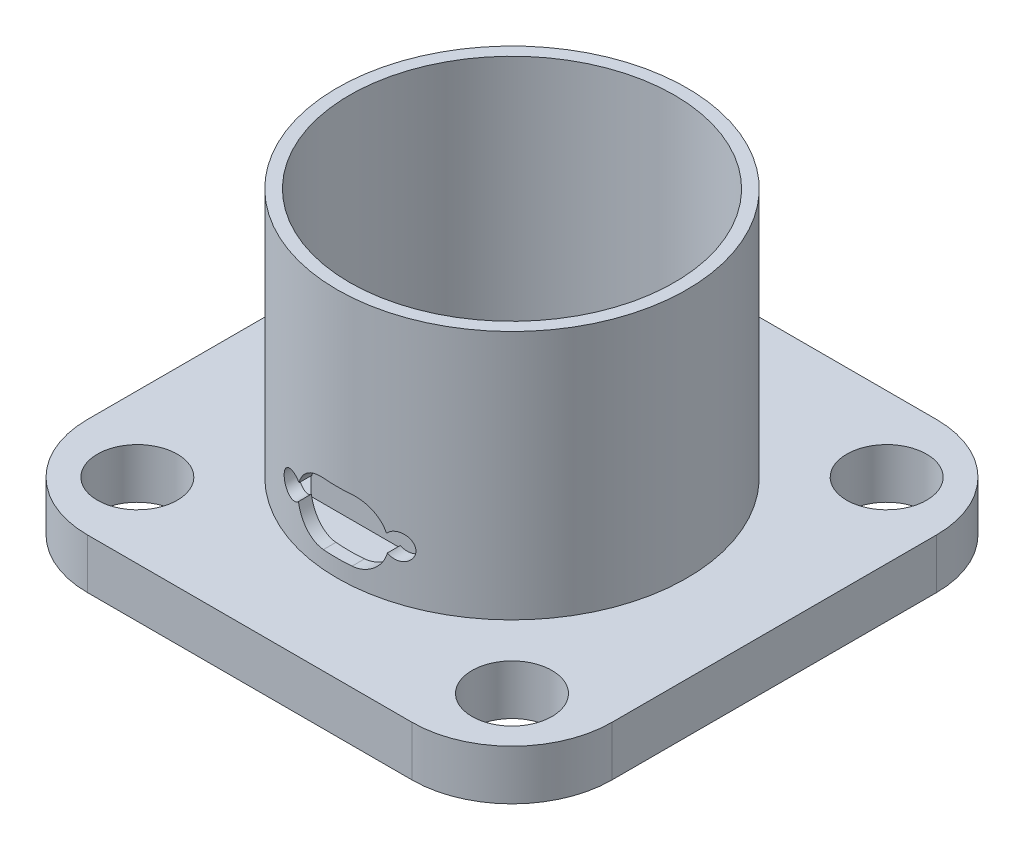
SolidWorks part; units mm, degrees
ref_plane "Front Plane" through (0, 0, 0) normal (0, 0, 1) x (1, 0, 0)
ref_plane "Top Plane" through (0, 0, 0) normal (0, 1, 0) x (1, 0, 0)
ref_plane "Right Plane" through (0, 0, 0) normal (1, 0, 0) x (0, 0, -1)
sketch "Sketch1" plane through (0, 0, 0) normal (0, 1, 0) x (1, 0, 0)
  line L1 (10.5, -10.5) -> (-10.5, -10.5)
  line L2 (10.5, -10.5) -> (10.5, 10.5)
  line L3 (10.5, 10.5) -> (-10.5, 10.5)
  line L4 (-10.5, -10.5) -> (-10.5, 10.5)
  line L5 (10.5, -10.5) -> (-10.5, 10.5) construction
  line L6 (10.5, 10.5) -> (-10.5, -10.5) construction
  point P0 (0, 0)
  dimension "D1" = 21
  dimension "D2" = 21
extrude "Boss-Extrude1" add sketch "Sketch1" along normal blind 2
sketch "Sketch2" plane through (0, 2, 0) normal (0, 1, 0) x (1, 0, 0)
  line L1 (7.5, -7.5) -> (-7.5, -7.5)
  line L2 (7.5, -7.5) -> (7.5, 7.5)
  line L3 (7.5, 7.5) -> (-7.5, 7.5)
  line L4 (-7.5, -7.5) -> (-7.5, 7.5)
  line L5 (7.5, -7.5) -> (-7.5, 7.5) construction
  line L6 (7.5, 7.5) -> (-7.5, -7.5) construction
  point P0 (0, 0)
  dimension "D1" = 15
  dimension "D2" = 15
sketch "Sketch3" plane through (0, 2, 0) normal (0, 1, 0) x (1, 0, 0)
  circle A0 centre (-7.5, 7.5) radius 1.6
  circle A1 centre (7.5, 7.5) radius 1.6
  circle A2 centre (7.5, -7.5) radius 1.6
  circle A3 centre (-7.5, -7.5) radius 1.6
  dimension "D1" = 3.2
sketch "Sketch4" plane through (0, 2, 0) normal (0, 1, 0) x (1, 0, 0)
  line L1 (-5.7615, -1.2708) -> (-6.6325, -1.2708)
  line L3 (-5.7705, 1.2292) -> (-6.6325, 1.2292)
  line L4 (-6.6325, -1.2708) -> (-6.6325, 1.2292)
  line L5 (-5.2678, -1.0609) -> (-6.6325, 1.2292) construction
  line L6 (-5.2922, 1.0544) -> (-6.6325, -1.2708) construction
  line L7 (5.7615, -1.2708) -> (6.6325, -1.2708)
  line L9 (5.7705, 1.2292) -> (6.6325, 1.2292)
  line L10 (6.6325, -1.2708) -> (6.6325, 1.2292)
  line L11 (5.1992, -1.1759) -> (6.6325, 1.2292) construction
  line L12 (5.2254, 1.1704) -> (6.6325, -1.2708) construction
  arc A0 (-5.7615, -1.2708) -> (5.7615, -1.2708) centre (0, 0) ccw
  arc A1 (5.7705, 1.2292) -> (-5.7705, 1.2292) centre (0, 0) ccw
  point P3 (-5.9, 0)
  point P8 (5.9, 0)
  dimension "D1" = 11.8
  dimension "D2" = 2.5
  dimension "D3" = 2.5
  dimension "D4" = 0.862
  dimension "D5" = 0.862
extrude "Boss-Extrude2" add sketch "Sketch4" against normal blind 2 from surface at -2 starting at face at (0, 0, 0)
extrude "Cut-Extrude1" cut sketch "Sketch3" against normal through all
sketch "Sketch5" plane through (0, 2, 0) normal (0, 1, 0) x (1, 0, 0)
  circle A0 centre (0, 0) radius 7
  dimension "D1" = 14
extrude "Boss-Extrude3" add sketch "Sketch5" along normal blind 10
sketch "Sketch6" plane through (0, 12, 0) normal (0, 1, 0) x (1, 0, 0)
  circle A0 centre (0, 0) radius 6.5
  circle A2 centre (0, 0) radius 7 construction
  dimension "D1" = 0.5
extrude "Cut-Extrude2" cut sketch "Sketch6" against normal up to surface (10 mm away) up to face at (0, 2, 7)
sketch "Sketch15" plane through (0, 2, 0) normal (0, 1, 0) x (1, 0, 0)
  circle A0 centre (7.5, 7.5) radius 3.1
  dimension "D1" = 6.2
ref_plane "Plane1" through (0, 0, 7) normal (0, 0, 1) x (1, 0, 0)
sketch "Sketch12" plane through (0, 0, 7) normal (0, 0, 1) x (1, 0, 0)
  line L0 (0.5735, 3.9321) -> (-0.5735, 3.9321) construction
  line L1 (0.5735, 2.6918) -> (-0.5735, 2.6918)
  line L2 (0.5735, 5.1723) -> (-0.5735, 5.1723)
  arc A0 (0.5735, 2.6918) -> (0.5735, 5.1723) centre (0.5735, 3.9321) ccw
  arc A1 (-0.5735, 5.1723) -> (-0.5735, 2.6918) centre (-0.5735, 3.9321) ccw
  point P2 (0, 3.9321)
extrude "Cut-Extrude3" cut sketch "Sketch12" against normal up to next
sketch "Sketch13" plane through (0, 2, 0) normal (0, 1, 0) x (1, 0, 0)
  line L8 (0, 0) -> (0, -6.5) construction
  line L33 (-2.85, -4.6901) -> (2.85, -4.6901)
  line L34 (-2.85, -4.6901) -> (-2.85, -4.1901) construction
  line L55 (-2.85, -4.1901) -> (2.85, -4.1901)
  line L56 (2.85, -4.6901) -> (2.85, -4.1901) construction
  line L57 (-2.85, -4.6901) -> (2.85, -4.1901) construction
  line L58 (-2.85, -4.1901) -> (2.85, -4.6901) construction
  line L59 (3.35, -4.6901) -> (3.35, -1.6901)
  line L60 (-2.85, -4.6901) -> (-3.35, -4.6901)
  line L61 (-2.85, -4.1901) -> (-2.85, -1.6901)
  line L62 (-2.85, -1.6901) -> (-3.35, -1.6901)
  line L63 (-3.35, -4.6901) -> (-3.35, -1.6901)
  line L64 (2.85, -1.6901) -> (3.35, -1.6901)
  line L65 (2.85, -4.1901) -> (2.85, -1.6901)
  line L66 (2.85, -4.6901) -> (3.35, -4.6901)
  line L67 (2.85, -4.6901) -> (2.85, -4.1901) construction
  line L68 (-2.85, -4.6901) -> (-2.85, -4.1901) construction
  line L69 (2.85, -4.6901) -> (2.85, -4.1901) construction
  circle A3 centre (0, 0) radius 6.5 construction
  point P0 (0, -4.4401)
  dimension "D1" = 5.7
  dimension "D3" = 0.5
  dimension "D4" = 3
  dimension "D2" = 0.5
extrude "Boss-Extrude4" add sketch "Sketch13" along normal blind 4
sketch "Sketch14" plane through (0, 0, 4.1901) normal (0, 0, -1) x (-1, 0, 0)
  line L0 (-2.85, 5.2782) -> (0, 5.2782) construction
  line L6 (-2.85, 6) -> (-2.85, 2) construction
  line L7 (0, 5.2782) -> (2.85, 5.2782) construction
  line L8 (2.85, 6) -> (2.85, 2) construction
  line L9 (-2.85, 4) -> (-1.425, 4) construction
  line L10 (-2.85, 6) -> (-2.85, 2) construction
  line L11 (-1.425, 4) -> (0, 4) construction
  line L12 (0, 4) -> (1.425, 4) construction
  line L13 (1.425, 4) -> (2.85, 4) construction
  circle A0 centre (-2.1375, 4) radius 0.5
  circle A1 centre (-0.7125, 4) radius 0.5
  circle A2 centre (0.7125, 4) radius 0.5
  circle A3 centre (2.1375, 4) radius 0.5
  dimension "D1" = 1
  dimension "D2" = 1
  dimension "D3" = 1
  dimension "D4" = 1
extrude "Cut-Extrude4" cut sketch "Sketch14" against normal blind 10
fillet "Fillet1" radius 4 4 edges at (10.5, 1, -10.5) (-10.5, 1, -10.5) (-10.5, 1, 10.5) (10.5, 1, 10.5)
equation "\"D4@Sketch14\"=\"D3@Sketch14\""
